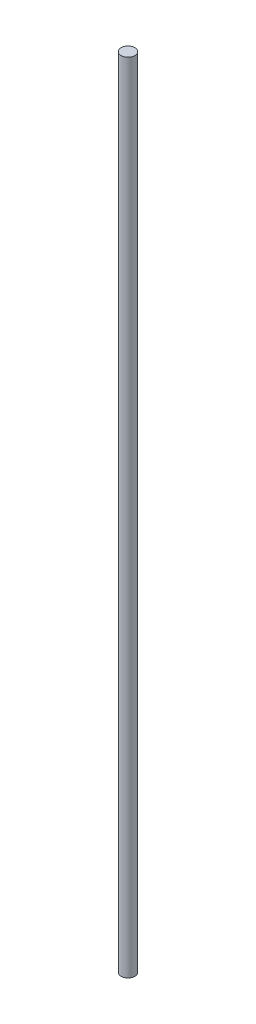
SolidWorks part; units mm, degrees
ref_plane "Plan de face" through (0, 0, 0) normal (0, 0, 1) x (1, 0, 0)
ref_plane "Plan de dessus" through (0, 0, 0) normal (0, 1, 0) x (1, 0, 0)
ref_plane "Plan de droite" through (0, 0, 0) normal (1, 0, 0) x (0, 0, -1)
sketch "Sketch1" plane through (0, 0, 0) normal (0, 1, 0) x (1, 0, 0)
  circle A0 centre (0, 0) radius 5
  dimension "D1" = 10
extrude "Boss-Extrude1" add sketch "Sketch1" along normal blind 580
